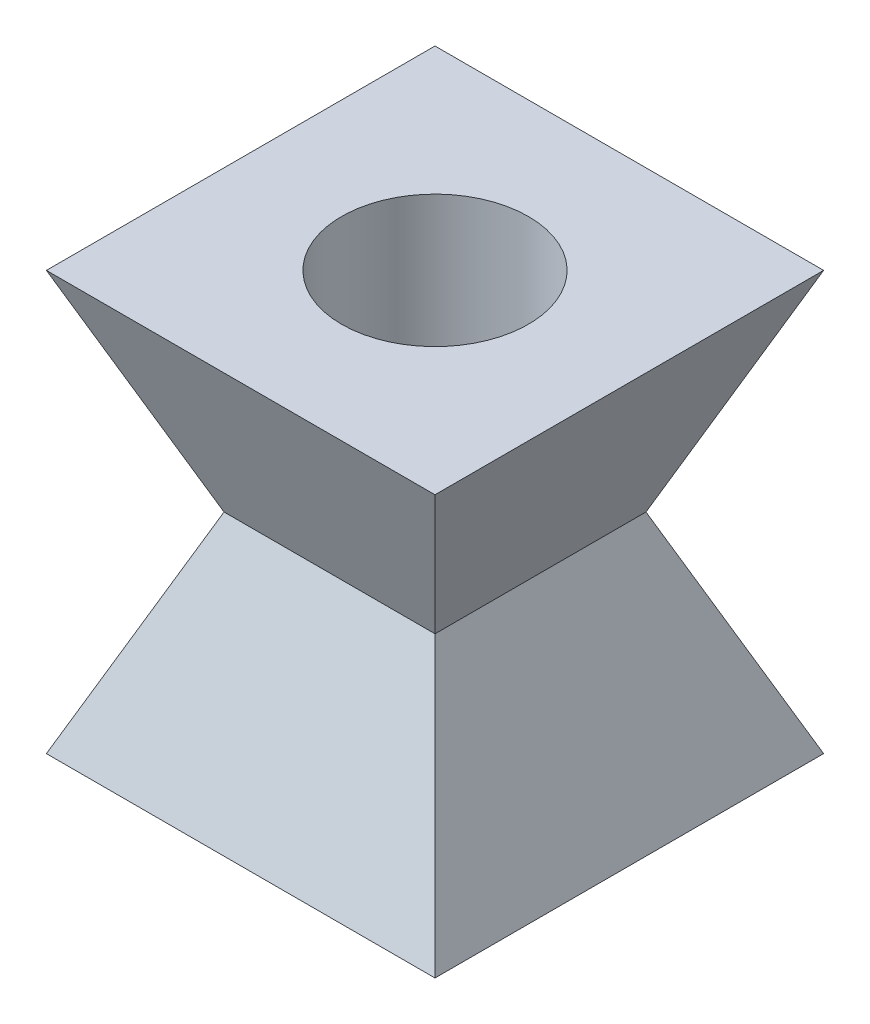
SolidWorks part; units mm, degrees
material "Acier inoxydable moulé"
ref_plane "Plan de face" through (0, 0, 0) normal (0, 0, 1) x (1, 0, 0)
ref_plane "Plan de dessus" through (0, 0, 0) normal (0, 1, 0) x (1, 0, 0)
ref_plane "Plan de droite" through (0, 0, 0) normal (1, 0, 0) x (0, 0, -1)
sketch "Esquisse1" plane through (0, 0, 0) normal (0, 1, 0) x (1, 0, 0)
  line L1 (-52, 52) -> (52, 52)
  line L2 (-52, 52) -> (-52, -52)
  line L3 (-52, -52) -> (52, -52)
  line L4 (52, 52) -> (52, -52)
  line L5 (-52, 52) -> (52, -52) construction
  line L6 (-52, -52) -> (52, 52) construction
  point P0 (0, 0)
  dimension "D1" = 104
  dimension "D2" = 104
extrude "Boss.-Extru.2" add sketch "Esquisse1" against normal blind 56 draft 23
mirror "Symétrie1" about plane through (0, -56, 0) normal (0, 1, 0) of "Boss.-Extru.2"
sketch "Esquisse2" plane through (0, 0, 0) normal (0, 1, 0) x (1, 0, 0)
  circle A0 centre (0, 0) radius 25
  dimension "D1" = 50
extrude "Enlèv. mat.-Extru.1" cut sketch "Esquisse2" against normal through all and the other way through all
equation "\"A\"= 112"
equation "\"B\"= 104"
equation "\"C\"= 23"
equation "\"D1@Esquisse1\"=\"B\""
equation "\"D2@Esquisse1\"=\"B\""
equation "\"D1@Boss.-Extru.2\"=\"A\" / 2"
equation "\"D3@Boss.-Extru.2\"=\"C\""
